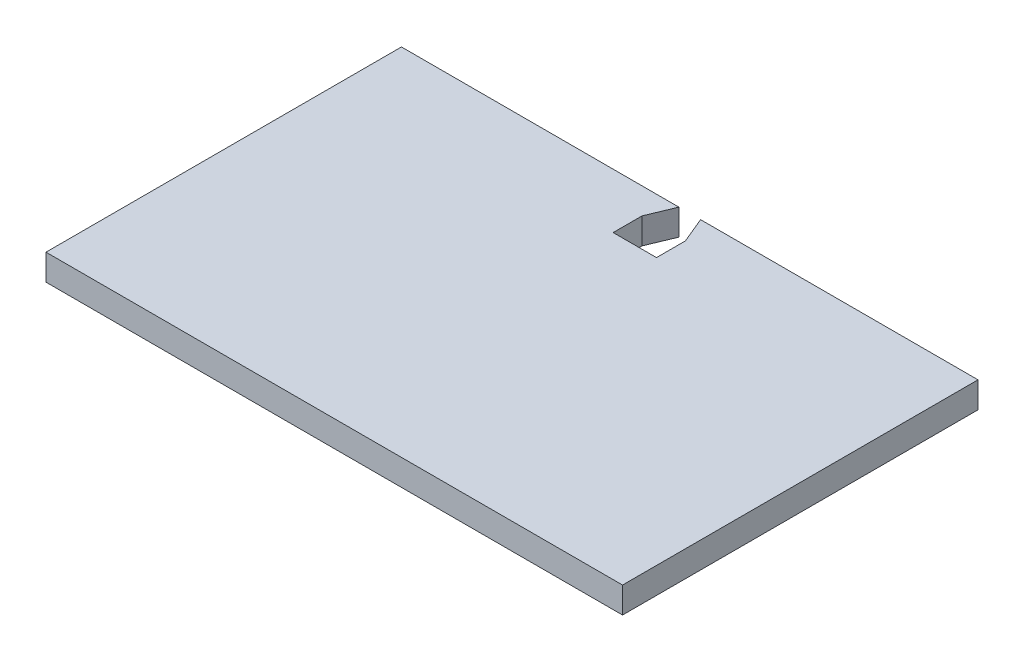
SolidWorks part; units mm, degrees
ref_plane "Front Plane" through (0, 0, 0) normal (0, 0, 1) x (1, 0, 0)
ref_plane "Top Plane" through (0, 0, 0) normal (0, 1, 0) x (1, 0, 0)
ref_plane "Right Plane" through (0, 0, 0) normal (1, 0, 0) x (0, 0, -1)
sketch "Sketch1" plane through (0, 0, 0) normal (0, 1, 0) x (1, 0, 0)
  line L1 (-172.9862, 68.0628) -> (226.0138, 68.0628)
  line L2 (-172.9862, 68.0628) -> (-172.9862, -177.9372)
  line L3 (-172.9862, -177.9372) -> (226.0138, -177.9372)
  line L4 (226.0138, 68.0628) -> (226.0138, -177.9372)
  line L5 (-172.9862, 68.0628) -> (226.0138, -177.9372) construction
  line L6 (-172.9862, -177.9372) -> (226.0138, 68.0628) construction
  point P4 (26.5138, -54.9372)
  dimension "D1" = 399
  dimension "D2" = 246
extrude "Boss-Extrude1" add sketch "Sketch1" along normal blind 18
sketch "Sketch2" plane through (0, 0, 0) normal (0, -1, 0) x (1, 0, 0)
  line L0 (-92.9862, 97.9372) -> (-92.9862, 11.9372)
  line L1 (-92.9862, 11.9372) -> (146.0138, 11.9372)
  line L2 (146.0138, 11.9372) -> (146.0138, 97.9372)
  line L3 (146.0138, 97.9372) -> (-92.9862, 97.9372)
extrude "Cut-Extrude1" cut sketch "Sketch2" against normal blind 6 contours L0 L1 L2 L3
sketch "Sketch3" plane through (0, 18, 0) normal (0, 1, 0) x (1, 0, 0)
  line L0 (11.5138, 50.0628) -> (41.5138, 50.0628) construction
  line L2 (19.0138, 68.0628) -> (34.0138, 68.0628)
  line L4 (-172.9862, 68.0628) -> (-172.9862, -177.9372)
  line L5 (-172.9862, -177.9372) -> (226.0138, -177.9372)
  line L6 (226.0138, -177.9372) -> (226.0138, 68.0628)
  line L7 (226.0138, 68.0628) -> (-172.9862, 68.0628)
  line L8 (-172.9862, 68.0628) -> (-172.9862, -177.9372)
  line L9 (-172.9862, -177.9372) -> (226.0138, -177.9372)
  line L10 (226.0138, -177.9372) -> (226.0138, 68.0628)
  line L11 (226.0138, 68.0628) -> (-172.9862, 68.0628)
  line L14 (11.5138, 50.0628) -> (11.5138, 30.0628)
  line L18 (11.5138, 30.0628) -> (41.5138, 30.0628)
  line L19 (41.5138, 50.0628) -> (41.5138, 30.0628)
  line L20 (26.5138, 48.0628) -> (26.5138, 40.5237) construction
  line L21 (34.0138, 68.0628) -> (41.5138, 50.0628)
  line L22 (19.0138, 68.0628) -> (11.5138, 50.0628)
  point P9 (30.2638, 63.0628)
  point P13 (34.0138, 53.0628)
  dimension "D2" = 18
  dimension "D1" = 0
extrude "Cut-Extrude2" cut sketch "Sketch3" against normal up to next
